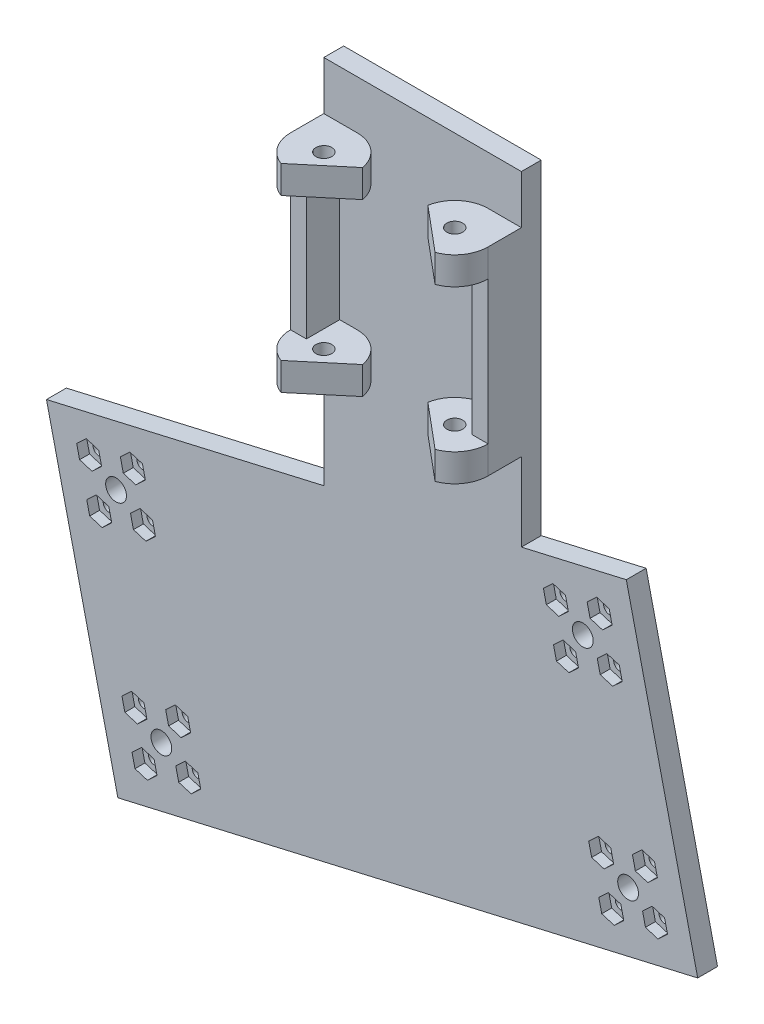
SolidWorks part; units mm, degrees
ref_plane "Front Plane" through (0, 0, 0) normal (0, 0, 1) x (1, 0, 0)
ref_plane "Top Plane" through (0, 0, 0) normal (0, 1, 0) x (1, 0, 0)
ref_plane "Right Plane" through (0, 0, 0) normal (1, 0, 0) x (0, 0, -1)
sketch "Sketch1" plane through (0, 0, 0) normal (0, 1, 0) x (1, 0, 0)
  line L0 (0, 22.8391) -> (0, -19.8342) construction
  line L1 (-35.1495, 0) -> (37.3645, 0) construction
  line L2 (-24.9, 0) -> (-24.9, 13.4)
  line L3 (-24.9, 13.4) -> (24.9, 13.4)
  line L4 (24.9, 0) -> (24.9, 13.4)
  line L5 (-19.4124, -7.879) -> (-8.235, 1.5)
  line L6 (19.4124, -7.879) -> (8.235, 1.5)
  line L7 (16.5, 8.4) -> (-16.5, 8.4)
  arc A0 (19.4124, -7.879) -> (24.9, 0) centre (16.5, 0) ccw
  arc A1 (-19.4124, -7.879) -> (-24.9, 0) centre (-16.5, 0) cw
  arc A2 (-16.5, 8.4) -> (-8.235, 1.5) centre (-16.5, 0) cw
  arc A3 (16.5, 8.4) -> (8.235, 1.5) centre (16.5, 0) ccw
  circle A4 centre (-16.5, 0) radius 8.4 construction
  circle A5 centre (16.5, 0) radius 8.4 construction
  point P14 (0, 13.4)
  dimension "D1" = 16.8
  dimension "D2" = 33
  dimension "D3" = 5
  dimension "D4" = 130
  dimension "D5" = 1.5
  dimension "D6" = 13.4
extrude "Boss-Extrude2" add sketch "Sketch1" along normal blind 7
sketch "Sketch3" plane through (0, 7, 0) normal (0, 1, 0) x (1, 0, 0)
  circle A0 centre (-16.5, 0) radius 2
  circle A1 centre (16.5, 0) radius 2
  dimension "D1" = 4
extrude "Cut-Extrude2" cut sketch "Sketch3" against normal through all both and the other way through all
sketch "Sketch4" plane through (0, 7, 0) normal (0, 1, 0) x (1, 0, 0)
  line L0 (-24.9, 13.4) -> (-24.9, 0)
  line L1 (-24.9, 13.4) -> (24.9, 13.4)
  line L2 (24.9, 13.4) -> (24.9, 0)
  line L3 (0, 13.4) -> (0, 0) construction
  line L4 (-16.5, 8.4) -> (16.5, 8.4)
  line L5 (-16.5, 8.4) -> (16.5, 8.4) construction
  line L6 (16.5, 8.4) -> (20.9, 8.4)
  line L7 (20.9, 8.4) -> (20.9, 0)
  line L8 (20.9, 0) -> (24.9, 0)
  line L9 (-20.9, 0) -> (-24.9, 0)
  line L10 (-20.9, 8.4) -> (-20.9, 0)
  line L11 (-16.5, 8.4) -> (-20.9, 8.4)
  circle A0 centre (-16.5, 0) radius 3.7 construction
  point P21 (0, 8.4)
  dimension "D2" = 7.4
  dimension "D1" = 4
extrude "Boss-Extrude3" add sketch "Sketch4" along normal blind 36
sketch "Sketch5" plane through (0, 43, 0) normal (0, 1, 0) x (1, 0, 0)
  line L12 (-24.9, 13.4) -> (-24.9, 0)
  line L13 (24.9, 13.4) -> (-24.9, 13.4)
  line L14 (24.9, 0) -> (24.9, 13.4)
  line L15 (8.235, 1.5) -> (19.4124, -7.879)
  line L16 (-16.5, 8.4) -> (16.5, 8.4)
  line L17 (-19.4124, -7.879) -> (-8.235, 1.5)
  line L18 (-24.9, 13.4) -> (-24.9, 0)
  line L19 (24.9, 13.4) -> (-24.9, 13.4)
  line L20 (24.9, 0) -> (24.9, 13.4)
  line L21 (8.235, 1.5) -> (19.4124, -7.879)
  line L22 (-16.5, 8.4) -> (16.5, 8.4)
  line L23 (-19.4124, -7.879) -> (-8.235, 1.5)
  circle A0 centre (-16.5, 0) radius 2 construction
  circle A1 centre (16.5, 0) radius 2
  circle A2 centre (16.5, 0) radius 2 construction
  circle A4 centre (-16.5, 0) radius 2
  arc A8 (-24.9, 0) -> (-19.4124, -7.879) centre (-16.5, 0) ccw
  arc A9 (19.4124, -7.879) -> (24.9, 0) centre (16.5, 0) ccw
  arc A10 (16.5, 8.4) -> (8.235, 1.5) centre (16.5, 0) ccw
  arc A11 (-8.235, 1.5) -> (-16.5, 8.4) centre (-16.5, 0) ccw
  arc A12 (-24.9, 0) -> (-19.4124, -7.879) centre (-16.5, 0) ccw
  arc A13 (19.4124, -7.879) -> (24.9, 0) centre (16.5, 0) ccw
  arc A14 (16.5, 8.4) -> (8.235, 1.5) centre (16.5, 0) ccw
  arc A15 (-8.235, 1.5) -> (-16.5, 8.4) centre (-16.5, 0) ccw
  dimension "D1" = 0
extrude "Boss-Extrude4" add sketch "Sketch5" along normal blind 7
sketch "Sketch13" plane through (0, 50, 0) normal (0, 1, 0) x (1, 0, 0)
  line L0 (24.9, 0) -> (24.9, 13.4) construction
  line L5 (-24.9, 13.4) -> (24.9, 13.4)
  line L6 (-24.9, 13.4) -> (-24.9, 8.4)
  line L7 (-24.9, 8.4) -> (24.9, 8.4)
  line L8 (24.9, 13.4) -> (24.9, 8.4)
  line L9 (-16.5, 8.4) -> (16.5, 8.4) construction
extrude "Boss-Extrude6" add sketch "Sketch13" along normal blind 12.25
sketch "Sketch15" plane through (0, 0, 0) normal (0, -1, 0) x (1, 0, 0)
  line L0 (24.9, 0) -> (24.9, -13.4) construction
  line L1 (-24.9, -13.4) -> (24.9, -13.4)
  line L2 (-24.9, -13.4) -> (-24.9, -8.4)
  line L3 (-24.9, -8.4) -> (24.9, -8.4)
  line L4 (24.9, -13.4) -> (24.9, -8.4)
  line L5 (-16.5, -8.4) -> (16.5, -8.4) construction
extrude "Boss-Extrude7" add sketch "Sketch15" along normal blind 30
sketch "Sketch12" plane through (0, 0, -13.4) normal (0, 0, -1) x (-1, 0, 0)
  line L8 (-24.9, -30) -> (19.5541, -30) construction
  line L9 (24.9, -30) -> (24.9, -31.2342) construction
  line L10 (24.9, -41.4972) -> (-24.9, -30) construction
  line L19 (0, -35.7486) -> (-6.7485, -64.9797) construction
  line L20 (2.2495, -26.0049) -> (-51.3408, -13.6326)
  line L21 (-24.9, -30) -> (-25.6851, -33.4006) construction
  line L22 (0, -35.7486) -> (5.7273, -10.9407) construction
  line L23 (2.2495, -26.0049) -> (19.5541, -30)
  line L24 (-51.3408, -13.6326) -> (-69.3369, -91.5822)
  line L25 (-69.3369, -91.5822) -> (-15.7466, -103.9545)
  line L26 (94.8147, -47.3753) -> (76.8186, -125.3249)
  line L27 (76.8186, -125.3249) -> (-15.7466, -103.9545)
  line L28 (-6.7485, -64.9797) -> (-39.5375, -57.4098) construction
  line L29 (24.9, -30) -> (24.9, -31.2342)
  line L30 (24.9, -30) -> (19.5541, -30)
  line L31 (24.9, -31.2342) -> (94.8147, -47.3753)
  line L32 (24.9, -31.2342) -> (24.9, -41.4972) construction
  line L33 (19.5541, -30) -> (24.9, -30) construction
  point P14 (19.2721, -30)
  point P16 (5.7273, -10.9407)
  point P18 (0, 0)
  point P21 (-25.6851, -33.4006)
  dimension "D1" = 13
  dimension "D2" = 30
  dimension "D3" = 80
  dimension "D4" = 55
  dimension "D5" = 95
extrude "Boss-Extrude8" add sketch "Sketch12" against normal blind 5
sketch "Sketch16" plane through (0, 0, -8.4) normal (0, 0, 1) x (1, 0, 0)
  line L0 (60.3389, -52.6074) -> (-85.8166, -86.3501) construction
  line L1 (51.3408, -13.6326) -> (69.3369, -91.5822) construction
  line L2 (-76.8186, -125.3249) -> (-94.8147, -47.3753) construction
  line L3 (-3.7408, -108.4535) -> (-21.7369, -30.5039) construction
  line L4 (69.3369, -91.5822) -> (-76.8186, -125.3249) construction
  line L5 (24.9, -19.737) -> (51.3408, -13.6326) construction
  line L6 (-24.9, -31.2342) -> (24.9, -19.737) construction
  line L7 (40.3806, -31.1727) -> (54.6308, -27.8828) construction
  line L8 (40.3806, -31.1727) -> (47.165, -35.412) construction
  line L16 (45.3602, -27.5948) -> (47.767, -25.3505) construction
  line L17 (47.767, -25.3505) -> (47.0268, -22.1439) construction
  line L18 (47.0268, -22.1439) -> (43.8797, -21.1817) construction
  line L19 (43.8797, -21.1817) -> (41.4728, -23.4261) construction
  line L20 (41.4728, -23.4261) -> (42.2131, -26.6327) construction
  line L21 (42.2131, -26.6327) -> (45.3602, -27.5948) construction
  circle A0 centre (40.3806, -31.1727) radius 2.625
  circle A4 centre (40.3806, -31.1727) radius 8 construction
  circle A22 centre (47.165, -35.412) radius 1.5
  circle A23 centre (36.1412, -37.9571) radius 1.5
  circle A24 centre (33.5962, -26.9333) radius 1.5
  circle A25 centre (44.6199, -24.3883) radius 1.5
  circle A26 centre (44.6199, -24.3883) radius 2.85 construction
  circle A27 centre (47.5575, -87.4063) radius 1.5
  circle A28 centre (45.0125, -76.3826) radius 1.5
  circle A29 centre (58.5812, -84.8613) radius 1.5
  circle A30 centre (56.0362, -73.8376) radius 1.5
  circle A31 centre (51.7969, -80.622) radius 2.625
  circle A32 centre (-73.0352, -51.5511) radius 1.5
  circle A33 centre (-84.059, -54.0962) radius 1.5
  circle A34 centre (-81.5139, -65.1199) radius 1.5
  circle A35 centre (-77.2746, -58.3355) radius 2.625
  circle A36 centre (-70.4902, -62.5749) radius 1.5
  circle A37 centre (-61.619, -101.0004) radius 1.5
  circle A38 centre (-72.6427, -103.5454) radius 1.5
  circle A39 centre (-70.0977, -114.5692) radius 1.5
  circle A40 centre (-65.8583, -107.7848) radius 2.625
  circle A41 centre (-59.0739, -112.0242) radius 1.5
  point P16 (0, 0)
  point P31 (40.3806, -31.1727)
  point P36 (40.3806, -31.1727)
  dimension "D1" = 5.25
  dimension "D4" = 16
  dimension "D5" = 45
  dimension "D6" = 3
  dimension "D2" = 14.625
  dimension "D3" = 14.625
  dimension "D10" = 5.7
  dimension "D7" = 4
extrude "Cut-Extrude3" cut sketch "Sketch16" against normal through all both and the other way through all
sketch "Sketch22" plane through (0, 0, -8.4) normal (0, 0, 1) x (1, 0, 0)
  line L0 (51.3408, -13.6326) -> (69.3369, -91.5822) construction
  line L1 (32.8559, -23.7268) -> (30.4491, -25.9712)
  line L2 (30.4491, -25.9712) -> (31.1894, -29.1777)
  line L3 (31.1894, -29.1777) -> (34.3365, -30.1399)
  line L4 (34.3365, -30.1399) -> (36.7433, -27.8955)
  line L5 (36.7433, -27.8955) -> (36.003, -24.6889)
  line L6 (36.003, -24.6889) -> (32.8559, -23.7268)
  line L7 (43.8797, -21.1817) -> (41.4728, -23.4261)
  line L8 (41.4728, -23.4261) -> (42.2131, -26.6327)
  line L9 (42.2131, -26.6327) -> (45.3602, -27.5948)
  line L10 (45.3602, -27.5948) -> (47.767, -25.3505)
  line L11 (47.767, -25.3505) -> (47.0268, -22.1439)
  line L12 (47.0268, -22.1439) -> (43.8797, -21.1817)
  line L13 (46.4247, -32.2055) -> (44.0179, -34.4499)
  line L14 (44.0179, -34.4499) -> (44.7582, -37.6564)
  line L15 (44.7582, -37.6564) -> (47.9053, -38.6186)
  line L16 (47.9053, -38.6186) -> (50.3121, -36.3742)
  line L17 (50.3121, -36.3742) -> (49.5718, -33.1676)
  line L18 (49.5718, -33.1676) -> (46.4247, -32.2055)
  line L19 (38.548, -35.7127) -> (35.4009, -34.7505)
  line L20 (35.4009, -34.7505) -> (32.9941, -36.9949)
  line L21 (32.9941, -36.9949) -> (33.7344, -40.2015)
  line L22 (33.7344, -40.2015) -> (36.8815, -41.1636)
  line L23 (36.8815, -41.1636) -> (39.2883, -38.9192)
  line L24 (39.2883, -38.9192) -> (38.548, -35.7127)
  line L25 (60.3389, -52.6074) -> (-85.8166, -86.3501) construction
  line L26 (-76.8186, -125.3249) -> (-94.8147, -47.3753) construction
  line L27 (-24.9, -31.2342) -> (24.9, -19.737) construction
  line L28 (-12.7389, -69.4787) -> (-3.7408, -108.4535) construction
  line L30 (47.4193, -74.1382) -> (48.1596, -77.3448)
  line L31 (44.2722, -73.1761) -> (47.4193, -74.1382)
  line L32 (41.8654, -75.4204) -> (44.2722, -73.1761)
  line L33 (42.6057, -78.627) -> (41.8654, -75.4204)
  line L34 (45.7528, -79.5892) -> (42.6057, -78.627)
  line L35 (48.1596, -77.3448) -> (45.7528, -79.5892)
  line L36 (50.7046, -88.3685) -> (48.2978, -90.6129)
  line L37 (49.9643, -85.162) -> (50.7046, -88.3685)
  line L38 (46.8172, -84.1998) -> (49.9643, -85.162)
  line L39 (44.4104, -86.4442) -> (46.8172, -84.1998)
  line L40 (45.1507, -89.6507) -> (44.4104, -86.4442)
  line L41 (48.2978, -90.6129) -> (45.1507, -89.6507)
  line L42 (61.7283, -85.8235) -> (59.3215, -88.0679)
  line L43 (60.9881, -82.6169) -> (61.7283, -85.8235)
  line L44 (57.841, -81.6548) -> (60.9881, -82.6169)
  line L45 (55.4341, -83.8992) -> (57.841, -81.6548)
  line L46 (56.1744, -87.1057) -> (55.4341, -83.8992)
  line L47 (59.3215, -88.0679) -> (56.1744, -87.1057)
  line L48 (59.1833, -74.7997) -> (56.7765, -77.0441)
  line L49 (58.443, -71.5932) -> (59.1833, -74.7997)
  line L50 (55.2959, -70.631) -> (58.443, -71.5932)
  line L51 (52.8891, -72.8754) -> (55.2959, -70.631)
  line L52 (53.6294, -76.082) -> (52.8891, -72.8754)
  line L53 (56.7765, -77.0441) -> (53.6294, -76.082)
  line L54 (69.3369, -91.5822) -> (-76.8186, -125.3249) construction
  line L55 (-73.2448, -113.607) -> (-72.5045, -116.8136)
  line L56 (-70.838, -111.3626) -> (-73.2448, -113.607)
  line L57 (-67.6909, -112.3248) -> (-70.838, -111.3626)
  line L58 (-66.9506, -115.5314) -> (-67.6909, -112.3248)
  line L59 (-69.3574, -117.7757) -> (-66.9506, -115.5314)
  line L60 (-72.5045, -116.8136) -> (-69.3574, -117.7757)
  line L61 (-62.221, -111.062) -> (-61.4808, -114.2685)
  line L62 (-59.8142, -108.8176) -> (-62.221, -111.062)
  line L63 (-56.6671, -109.7798) -> (-59.8142, -108.8176)
  line L64 (-55.9268, -112.9863) -> (-56.6671, -109.7798)
  line L65 (-58.3337, -115.2307) -> (-55.9268, -112.9863)
  line L66 (-61.4808, -114.2685) -> (-58.3337, -115.2307)
  line L67 (-75.7898, -102.5833) -> (-75.0495, -105.7898)
  line L68 (-73.383, -100.3389) -> (-75.7898, -102.5833)
  line L69 (-70.2359, -101.3011) -> (-73.383, -100.3389)
  line L70 (-69.4956, -104.5076) -> (-70.2359, -101.3011)
  line L71 (-71.9024, -106.752) -> (-69.4956, -104.5076)
  line L72 (-75.0495, -105.7898) -> (-71.9024, -106.752)
  line L73 (-62.3593, -97.7939) -> (-64.7661, -100.0383)
  line L74 (-59.2122, -98.756) -> (-62.3593, -97.7939)
  line L75 (-58.4719, -101.9626) -> (-59.2122, -98.756)
  line L76 (-60.8787, -104.207) -> (-58.4719, -101.9626)
  line L77 (-64.0258, -103.2448) -> (-60.8787, -104.207)
  line L78 (-64.7661, -100.0383) -> (-64.0258, -103.2448)
  line L79 (-72.897, -64.8193) -> (-73.6373, -61.6127)
  line L80 (-69.7499, -65.7814) -> (-72.897, -64.8193)
  line L81 (-67.3431, -63.537) -> (-69.7499, -65.7814)
  line L82 (-68.0834, -60.3305) -> (-67.3431, -63.537)
  line L83 (-71.2305, -59.3683) -> (-68.0834, -60.3305)
  line L84 (-73.6373, -61.6127) -> (-71.2305, -59.3683)
  line L85 (-76.1823, -50.589) -> (-73.7755, -48.3446)
  line L86 (-75.4421, -53.7955) -> (-76.1823, -50.589)
  line L87 (-72.295, -54.7577) -> (-75.4421, -53.7955)
  line L88 (-69.8881, -52.5133) -> (-72.295, -54.7577)
  line L89 (-70.6284, -49.3067) -> (-69.8881, -52.5133)
  line L90 (-73.7755, -48.3446) -> (-70.6284, -49.3067)
  line L91 (-84.661, -64.1577) -> (-82.2542, -61.9134)
  line L92 (-83.9208, -67.3643) -> (-84.661, -64.1577)
  line L93 (-80.7737, -68.3265) -> (-83.9208, -67.3643)
  line L94 (-78.3668, -66.0821) -> (-80.7737, -68.3265)
  line L95 (-79.1071, -62.8755) -> (-78.3668, -66.0821)
  line L96 (-82.2542, -61.9134) -> (-79.1071, -62.8755)
  line L97 (-87.2061, -53.134) -> (-84.7993, -50.8896)
  line L98 (-86.4658, -56.3406) -> (-87.2061, -53.134)
  line L99 (-83.3187, -57.3027) -> (-86.4658, -56.3406)
  line L100 (-80.9119, -55.0583) -> (-83.3187, -57.3027)
  line L101 (-81.6522, -51.8518) -> (-80.9119, -55.0583)
  line L102 (-84.7993, -50.8896) -> (-81.6522, -51.8518)
  circle A0 centre (33.5962, -26.9333) radius 2.85 construction
  circle A1 centre (44.6199, -24.3883) radius 2.85 construction
  circle A2 centre (47.165, -35.412) radius 2.85 construction
  circle A3 centre (36.1412, -37.9571) radius 2.85 construction
  dimension "D1" = 5.7
  dimension "D2" = 5.7
  dimension "D3" = 5.7
  dimension "D4" = 5.7
extrude "Cut-Extrude8" cut sketch "Sketch22" against normal blind 2.5
sketch "Sketch31" plane through (0, 0, -13.4) normal (0, 0, -1) x (-1, 0, 0)
  line L0 (-24.9, -19.737) -> (24.9, -31.2342) construction
  line L1 (-60.3389, -52.6074) -> (85.8166, -86.3501) construction
  line L2 (-51.3408, -13.6326) -> (-69.3369, -91.5822) construction
  line L3 (76.8186, -125.3249) -> (94.8147, -47.3753) construction
  line L4 (3.7408, -108.4535) -> (21.7369, -30.5039) construction
  line L5 (-69.3369, -91.5822) -> (76.8186, -125.3249) construction
  line L6 (12.7389, -69.4787) -> (0, -66.5377) construction
  line L8 (0, 62.25) -> (0, -132.1946) construction
  line L9 (-24.9, 62.25) -> (24.9, 62.25) construction
  point P16 (0, -66.5377)
